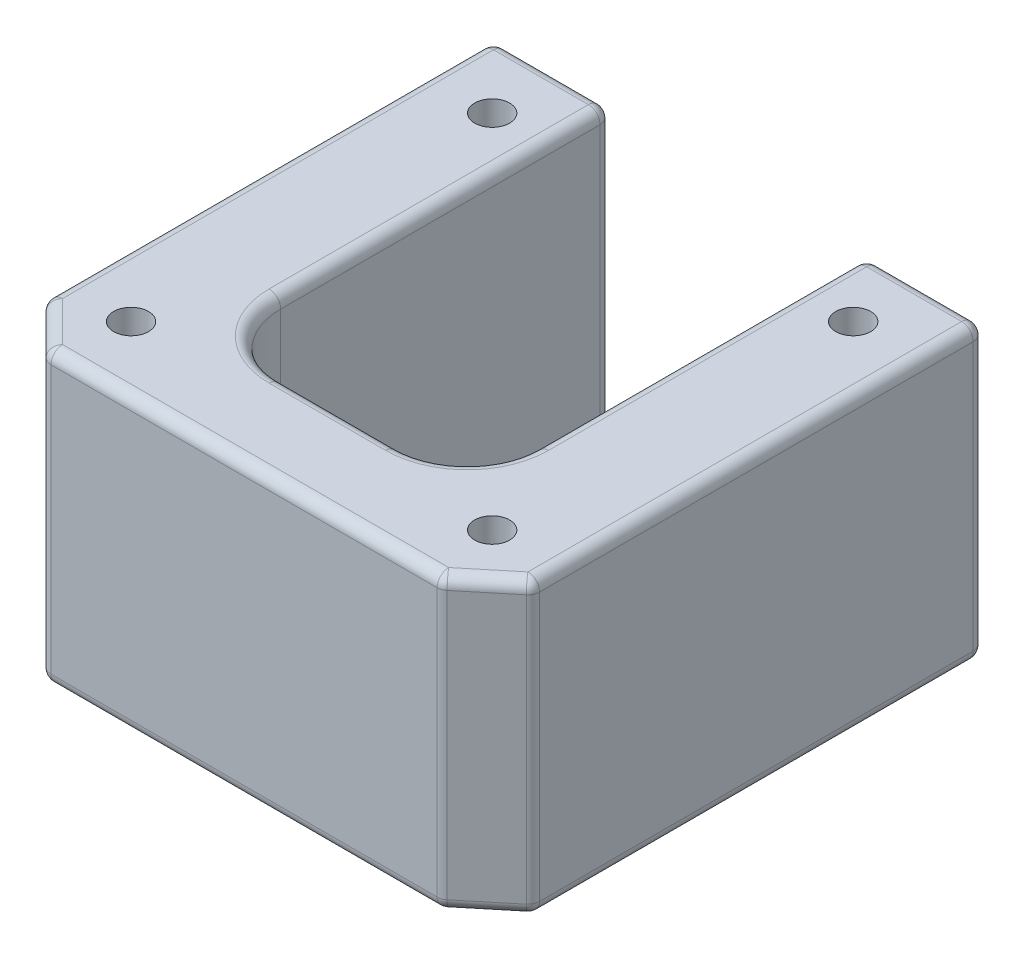
SolidWorks part; units mm, degrees
ref_plane "Front Plane" through (0, 0, 0) normal (0, 0, 1) x (1, 0, 0)
ref_plane "Top Plane" through (0, 0, 0) normal (0, 1, 0) x (1, 0, 0)
ref_plane "Right Plane" through (0, 0, 0) normal (1, 0, 0) x (0, 0, -1)
sketch "Sketch1" plane through (0, 0, 0) normal (0, 1, 0) x (1, 0, 0)
  line L1 (-10.2553, 3.0084) -> (11.7447, 3.0084)
  line L2 (-20.4053, 3.0084) -> (-20.4053, -4.9916)
  line L3 (-20.4053, -4.9916) -> (21.8947, -4.9916)
  line L4 (21.8947, 2.8971) -> (21.8947, -4.9916)
  line L5 (0, 0) -> (21.8947, -4.9916) construction
  line L6 (-20.4053, -4.9916) -> (0, 0) construction
  line L8 (-20.4053, 3.0084) -> (-20.4053, 37.4197)
  line L9 (-20.4053, 37.4197) -> (-10.2553, 37.4197)
  line L10 (-10.2553, 3.0084) -> (-10.2553, 37.4197)
  line L12 (21.8947, 2.8971) -> (21.8947, 37.3084)
  line L13 (21.8947, 37.3084) -> (11.7447, 37.3084)
  line L14 (11.7447, 3.0084) -> (11.7447, 37.3084)
  point P0 (0, 0)
  point P14 (0, 0)
  dimension "D1" = 42.3
  dimension "D2" = 42.3
  dimension "D3" = 22
  dimension "D4" = 8
extrude "Boss-Extrude1" add sketch "Sketch1" along normal blind 25
sketch "Sketch2" plane through (0, 0, 0) normal (0, -1, 0) x (1, 0, 0)
  line L1 (-20.4053, 4.9916) -> (21.8947, 4.9916) construction
  line L2 (21.8947, 4.9916) -> (21.8947, -37.3084) construction
  circle A0 centre (-14.7553, -31.6584) radius 1.5
  circle A1 centre (-14.7553, -0.6584) radius 1.5
  circle A2 centre (16.2447, -0.6584) radius 1.5
  circle A3 centre (16.2447, -31.6584) radius 1.5
  dimension "D5" = 3
  dimension "D1" = 31
  dimension "D2" = 31
  dimension "D3" = 5.65
  dimension "D4" = 5.65
extrude "Cut-Extrude1" cut sketch "Sketch2" against normal through all
fillet "Fillet1" radius 6 2 edges at (-10.2553, 12.5, -3.0084) (11.7447, 12.5, -3.0084)
sketch "Sketch3" plane through (0, 0, 0) normal (0, -1, 0) x (1, 0, 0)
  line L0 (21.8947, 1.3913) -> (17.5274, 4.9916)
  line L1 (21.8947, 4.9916) -> (21.8947, -37.3084) construction
  line L2 (-20.4053, 4.9916) -> (21.8947, 4.9916) construction
  line L3 (17.5274, 4.9916) -> (21.8947, 4.9916)
  line L4 (21.8947, 4.9916) -> (21.8947, 1.3913)
  line L5 (-20.4053, 0.9947) -> (-16.3978, 4.9916)
  line L6 (-20.4053, -37.4197) -> (-20.4053, 4.9916) construction
  line L7 (-16.3978, 4.9916) -> (-20.4053, 4.9916)
  line L8 (-20.4053, 4.9916) -> (-20.4053, 0.9947)
  dimension "D1" = 5.66
extrude "Cut-Extrude2" cut sketch "Sketch3" against normal through all
fillet "Fillet2" radius 1 32 edges at (-16.3978, 12.5, 4.9916) (-10.2553, 25, -23.214) (-8.4979, 25, -4.7658) (0.7447, 25, -3.0084) (9.9873, 25, -4.7658) (11.7447, 25, -23.1584) (21.8947, 25, -17.9586) (19.7111, 25, 3.1914) (0.5648, 25, 4.9916) (-18.4015, 25, 2.9931) (19.7111, 0, 3.1914) (21.8947, 0, -17.9586) (11.7447, 0, -23.1584) (9.9873, 0, -4.7658) (0.7447, 0, -3.0084) (-8.4979, 0, -4.7658) (-10.2553, 0, -23.214) (-18.4015, 0, 2.9931) (0.5648, 0, 4.9916) (21.8947, 12.5, -37.3084) (16.8197, 25, -37.3084) (11.7447, 12.5, -37.3084) (16.8197, 0, -37.3084) (-10.2553, 12.5, -37.4197) (-15.3303, 25, -37.4197) (-15.3303, 0, -37.4197) (-20.4053, 12.5, -37.4197) (-20.4053, 25, -18.2125) (-20.4053, 12.5, 0.9947) (-20.4053, 0, -18.2125) (17.5274, 12.5, 4.9916) (21.8947, 12.5, 1.3913)
equation "\"26..50mm\"=27"
